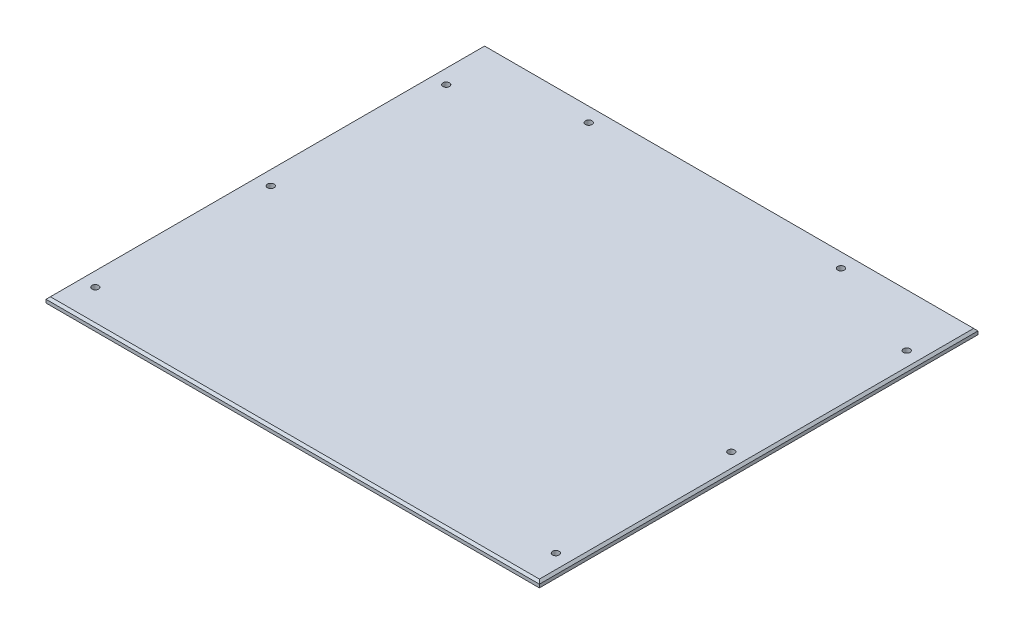
SolidWorks part; units mm, degrees
ref_plane "Alzado" through (0, 0, 0) normal (0, 0, 1) x (1, 0, 0)
ref_plane "Planta" through (0, 0, 0) normal (0, 1, 0) x (1, 0, 0)
ref_plane "Vista lateral" through (0, 0, 0) normal (1, 0, 0) x (0, 0, -1)
sketch "Croquis1" plane through (0, 0, 0) normal (0, 1, 0) x (1, 0, 0)
  line L1 (-188.3268, 170.428) -> (261.6732, 170.428)
  line L2 (-188.3268, 170.428) -> (-188.3268, -229.572)
  line L3 (-188.3268, -229.572) -> (261.6732, -229.572)
  line L4 (261.6732, 170.428) -> (261.6732, -229.572)
  circle A0 centre (-173.3268, 120.428) radius 3
  circle A1 centre (-173.3268, -199.572) radius 3
  circle A2 centre (246.6732, -199.572) radius 3
  circle A3 centre (246.6732, 120.428) radius 3
  circle A4 centre (-173.3268, -39.572) radius 3
  circle A5 centre (246.6732, -39.572) radius 3
  circle A6 centre (-78.3268, 155.428) radius 3
  circle A7 centre (151.6732, 155.428) radius 3
  dimension "D3" = 6
  dimension "D4" = 6
  dimension "D5" = 6
  dimension "D6" = 6
  dimension "D7" = 6
  dimension "D8" = 6
  dimension "D14" = 6
  dimension "D15" = 6
  dimension "D1" = 450
  dimension "D2" = 400
  dimension "D9" = 50
  dimension "D10" = 30
  dimension "D11" = 160
  dimension "D12" = 15
  dimension "D13" = 15
  dimension "D16" = 110
  dimension "D17" = 110
  dimension "D18" = 15
extrude "Saliente-Extruir1" add sketch "Croquis1" along normal blind 5
chamfer "Chaflán1" distance 2 angle 45 4 edges at (261.6732, 5, 29.572) (36.6732, 5, -170.428) (-188.3268, 5, 29.572) (36.6732, 5, 229.572)
